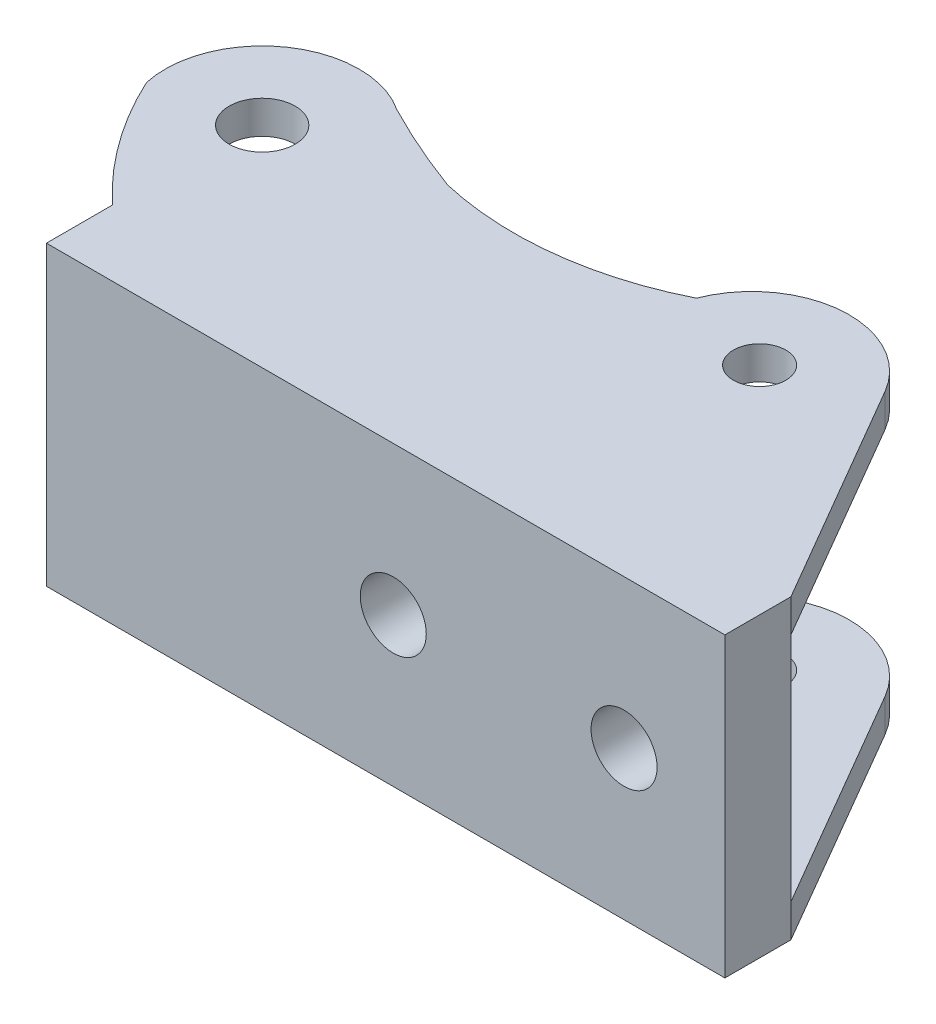
SolidWorks part; units mm, degrees
material "AISI 1020 Steel, Cold Rolled"
ref_plane "Front Plane" through (0, 0, 0) normal (0, 0, 1) x (1, 0, 0)
ref_plane "Top Plane" through (0, 0, 0) normal (0, 1, 0) x (1, 0, 0)
ref_plane "Right Plane" through (0, 0, 0) normal (1, 0, 0) x (0, 0, -1)
sketch "Sketch2" plane through (0, 0, 0) normal (0, 0, 1) x (1, 0, 0)
  line L0 (32.7414, 22.5) -> (32.7414, -22.5)
  line L1 (32.7414, -22.5) -> (-70, -22.5)
  line L2 (-70, -22.5) -> (-70, 22.5)
  line L3 (-70, 22.5) -> (32.7414, 22.5)
  circle A0 centre (17.475, 0) radius 5
  circle A1 centre (-17.475, 0) radius 5
  point P10 (32.7414, 0)
  dimension "D1" = 22.5
  dimension "D2" = 10
  dimension "D8" = 32.7414
  dimension "D4" = 45
  dimension "D6" = 17.475
  dimension "D7" = 17.475
  dimension "D9" = 70
extrude "Boss-Extrude1" add sketch "Sketch2" along normal blind 10
ref_plane "Plane1" through (0, 22.5, 0) normal (0, 1, 0) x (1, 0, 0)
sketch "Sketch3" plane through (0, 22.5, 0) normal (0, 1, 0) x (1, 0, 0)
  line L0 (32.7414, -10) -> (32.7414, 0)
  line L1 (32.7414, 0) -> (12.9418, 34.0513)
  line L2 (-70, 0) -> (-70, -10)
  line L3 (-70, -10) -> (32.7414, -10)
  arc A0 (12.9418, 34.0513) -> (-13.5715, 32) centre (0.1799, 26.6307) ccw
  arc A1 (-70, 0) -> (-83.493, 18.6549) centre (-29.0338, 43.838) cw
  arc A3 (-60.9969, 34.0513) -> (-47.2307, 28) centre (-5.7886, 140.9621) ccw
  arc A4 (-47.2307, 28) -> (-13.5715, 32) centre (-35.9522, 76.7114) ccw
  circle A5 centre (-69.1357, 21.81) radius 5
  circle A6 centre (0, 28) radius 3.9688
  arc A7 (-83.493, 18.6549) -> (-60.9969, 34.0513) centre (-69.1357, 21.81) cw
  dimension "D2" = 60
  dimension "D3" = 50
  dimension "D4" = 14.7
  dimension "D5" = 0.1799
  dimension "D6" = 7.9375
  dimension "D10" = 14.7625
  dimension "D11" = 120.3241
  dimension "D17" = 10
  dimension "D1" = 42
  dimension "D7" = 5.7886
  dimension "D8" = 28
  dimension "D9" = 29.0338
  dimension "D12" = 12.9418
  dimension "D13" = 35.9522
  dimension "D14" = 47.2307
  dimension "D15" = 60.9969
  dimension "D16" = 69.1357
extrude "Boss-Extrude2" add sketch "Sketch3" against normal blind 5
ref_plane "Plane2" through (0, -22.5, 0) normal (0, 1, 0) x (1, 0, 0)
mirror "Mirror1" about plane through (0, 0, 0) normal (0, 1, 0) of "Boss-Extrude2"
sketch3d "3DSketch1"
  line L0 (0, 22.5, -28) -> (0, -22.5, -28) construction
  line L1 (-69.1357, 22.5, -21.81) -> (-69.1357, -22.5, -21.81) construction
  point P3 (0, 0, -28)
  point P4 (0, 22.5, -28)
  point P9 (-69.1357, 0, -21.81)
